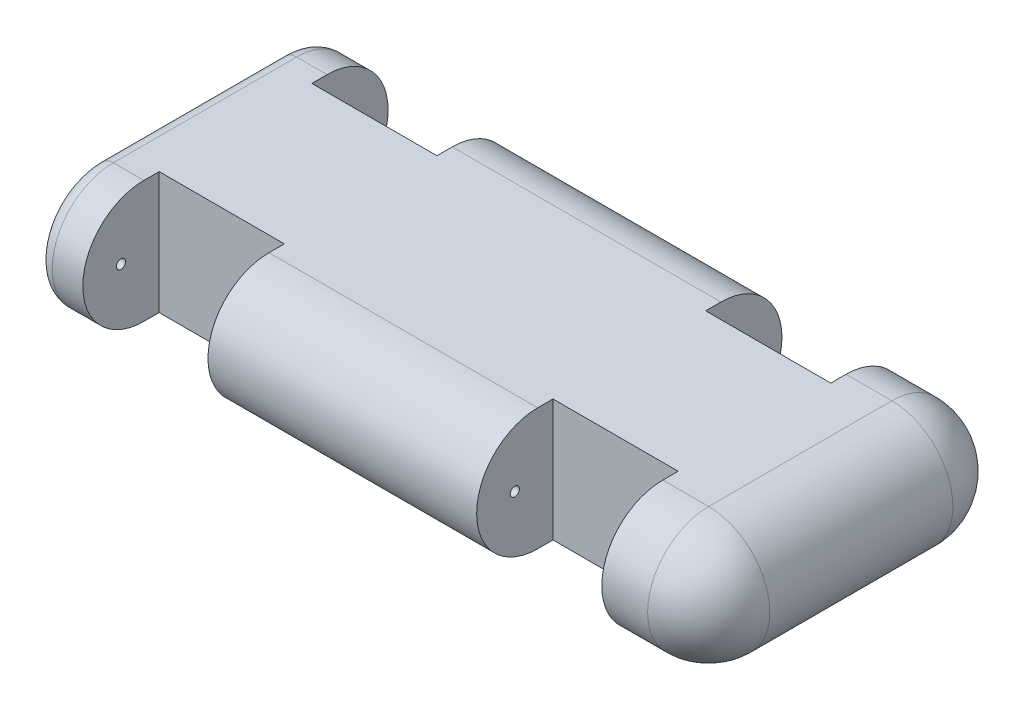
SolidWorks part; units mm, degrees
ref_plane "Front Plane" through (0, 0, 0) normal (0, 0, 1) x (1, 0, 0)
ref_plane "Top Plane" through (0, 0, 0) normal (0, 1, 0) x (1, 0, 0)
ref_plane "Right Plane" through (0, 0, 0) normal (1, 0, 0) x (0, 0, -1)
sketch "Sketch1" plane through (0, 0, 0) normal (0, 1, 0) x (1, 0, 0)
  line L0 (-88, -50) -> (88, -50) construction
  line L1 (-200, 100) -> (-170, 100)
  line L2 (-200, 100) -> (-200, -100)
  line L3 (-200, -100) -> (-170, -100)
  line L4 (200, 100) -> (200, -100)
  line L6 (-170, 100) -> (-170, 50)
  line L7 (-170, 50) -> (-88, 50)
  line L8 (-88, 100) -> (-88, 50)
  line L10 (88, 100) -> (88, 50)
  line L11 (88, 50) -> (170, 50)
  line L12 (170, 100) -> (170, 50)
  line L14 (-170, -100) -> (-170, -50)
  line L15 (-170, -50) -> (-88, -50)
  line L16 (-88, -100) -> (-88, -50)
  line L18 (88, -100) -> (88, -50)
  line L19 (88, -50) -> (170, -50)
  line L20 (170, -100) -> (170, -50)
  line L21 (-88, 50) -> (88, 50) construction
  line L22 (-170, -50) -> (-170, 50) construction
  line L23 (-88, 100) -> (88, 100)
  line L24 (170, 100) -> (200, 100)
  line L25 (170, -100) -> (200, -100)
  line L26 (-88, -100) -> (88, -100)
  point P20 (0, -50)
  point P23 (200, 0)
  point P24 (-170, 0)
  dimension "D1" = 82
  dimension "D2" = 30
  dimension "D3" = 400
  dimension "D4" = 100
  dimension "D5" = 50
extrude "Boss-Extrude1" add sketch "Sketch1" along normal mid plane 80
sketch "Sketch2" plane through (-88, 0, 0) normal (-1, 0, 0) x (0, 0, 1)
  line L0 (-100, 40) -> (-100, -40) construction
  circle A0 centre (-75, 0) radius 3
  dimension "D2" = 6
  dimension "D1" = 25
extrude "Cut-Extrude1" cut sketch "Sketch2" against normal through all both and the other way through all
sketch "Sketch3" plane through (-88, 0, 0) normal (-1, 0, 0) x (0, 0, 1)
  line L0 (100, 40) -> (100, -40) construction
  circle A0 centre (75, 0) radius 3
  dimension "D1" = 6
  dimension "D2" = 25
extrude "Cut-Extrude2" cut sketch "Sketch3" against normal through all both and the other way through all
sketch "Sketch4" plane through (-200, 0, 0) normal (-1, 0, 0) x (0, 0, 1)
  line L0 (-100, 40) -> (-100, -40) construction
  line L1 (-60, -40) -> (-60, -70.29)
  line L2 (-136.8642, 63.9422) -> (-60, 63.9422)
  line L3 (-136.8642, 63.9422) -> (-136.8642, -70.29)
  line L4 (-136.8642, -70.29) -> (-60, -70.29)
  line L5 (-60, 63.9422) -> (-60, 40)
  arc A0 (-60, 40) -> (-60, -40) centre (-60, 0) ccw
  dimension "D1" = 80
extrude "Cut-Extrude3" cut sketch "Sketch4" against normal through all both
sketch "Sketch5" plane through (-200, 0, 0) normal (-1, 0, 0) x (0, 0, 1)
  line L0 (100, 40) -> (100, -40) construction
  line L1 (60, -40) -> (60, -76.3281)
  line L2 (60, 68.8966) -> (141.0543, 68.8966)
  line L3 (60, 68.8966) -> (60, 40)
  line L4 (60, -76.3281) -> (141.0543, -76.3281)
  line L5 (141.0543, 68.8966) -> (141.0543, -76.3281)
  arc A0 (60, -40) -> (60, 40) centre (60, 0) ccw
  dimension "D1" = 80
extrude "Cut-Extrude4" cut sketch "Sketch5" against normal through all both
sketch "Sketch7" plane through (0, 0, 0) normal (0, 0, 1) x (1, 0, 0)
  line L0 (200, 40) -> (170, 40) construction
  line L1 (200, -40) -> (170, -40) construction
  line L2 (200, -3) -> (200, 3) construction
  line L3 (200, 40) -> (200, -40)
  arc A0 (200, -40) -> (200, 40) centre (200, 0) ccw
extrude "Boss-Extrude3" add sketch "Sketch7" along normal mid plane 120
sketch "Sketch8" plane through (0, 0, 60) normal (0, 0, 1) x (1, 0, 0)
  line L0 (200, 40) -> (200, -40)
  arc A0 (200, -40) -> (200, 40) centre (200, 0) ccw
  arc A1 (200, -40) -> (200, 40) centre (200, 0) ccw construction
revolve "Revolve1" add sketch "Sketch8" angle 90 about L0
mirror "Mirror1" about plane through (0, 0, 0) normal (0, 0, 1) of "Revolve1"
fillet "Fillet1" radius 10 4 edges at (-200, 0, -100) (-200, -40, 0) (-200, 0, 100) (-200, 40, 0)
